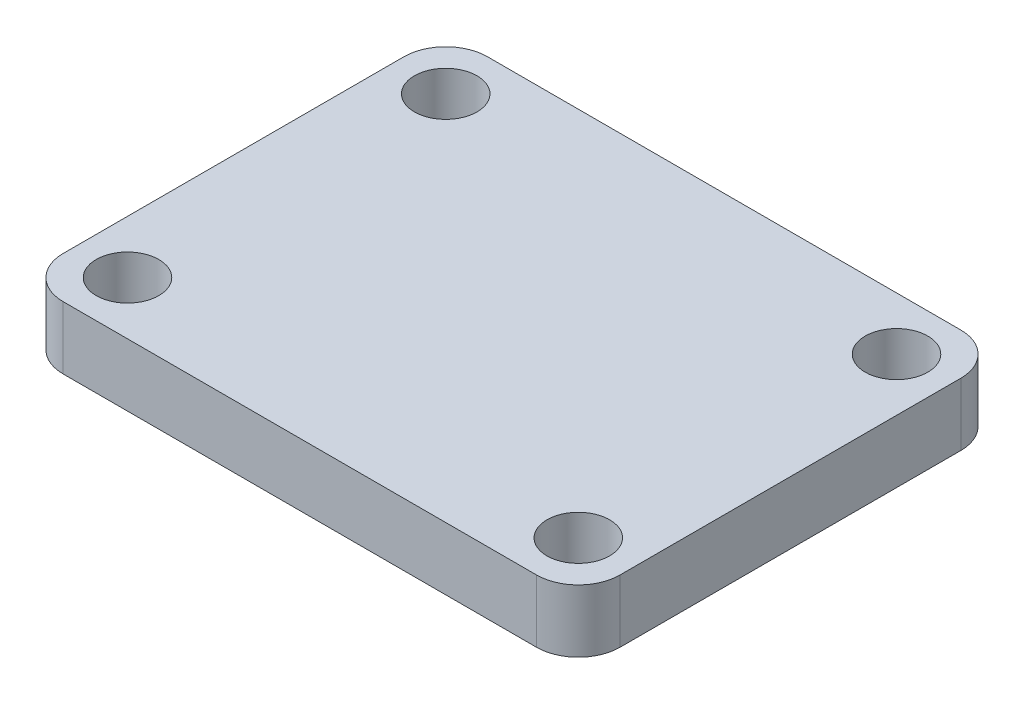
SolidWorks part; units mm, degrees
material "Fibra de vidrio-E"
ref_plane "Alzado" through (0, 0, 0) normal (0, 0, 1) x (1, 0, 0)
ref_plane "Planta" through (0, 0, 0) normal (0, 1, 0) x (1, 0, 0)
ref_plane "Vista lateral" through (0, 0, 0) normal (1, 0, 0) x (0, 0, -1)
sketch "Croquis1" plane through (0, 0, 0) normal (0, 1, 0) x (1, 0, 0)
  line L1 (0, 0) -> (26.67, 0)
  line L2 (0, 0) -> (0, 20.32)
  line L3 (0, 20.32) -> (26.67, 20.32)
  line L4 (26.67, 0) -> (26.67, 20.32)
  dimension "D1" = 20.32
  dimension "D2" = 26.67
extrude "Saliente-Extruir1" add sketch "Croquis1" along normal blind 3 contours L2 L1 L4 L3
sketch "Croquis2" plane through (0, 3, 0) normal (0, 1, 0) x (1, 0, 0)
  line L0 (13.335, 0) -> (13.335, 20.32) construction
  line L1 (0, 0) -> (26.67, 0) construction
  line L2 (0, 20.32) -> (26.67, 20.32) construction
  line L3 (0, 0) -> (0, 20.32) construction
  line L4 (26.67, 0) -> (26.67, 20.32) construction
  circle A0 centre (24.13, 2.54) radius 1.5
  circle A1 centre (2.54, 2.54) radius 1.5
  circle A2 centre (2.54, 17.78) radius 1.5
  circle A3 centre (24.13, 17.78) radius 1.5
  dimension "D1" = 2.54
  dimension "D2" = 2.54
  dimension "D3" = 2.54
  dimension "D4" = 2.54
  dimension "D5" = 2.54
  dimension "D6" = 2.54
  dimension "D7" = 2.54
  dimension "D8" = 2.54
  dimension "D9" = 3
  dimension "D10" = 3
  dimension "D11" = 3
  dimension "D12" = 3
extrude "Cortar-Extruir1" cut sketch "Croquis2" against normal through all
fillet "Redondeo1" radius 2 4 edges at (26.67, 1.5, -20.32) (26.67, 1.5, 0) (0, 1.5, 0) (0, 1.5, -20.32)
